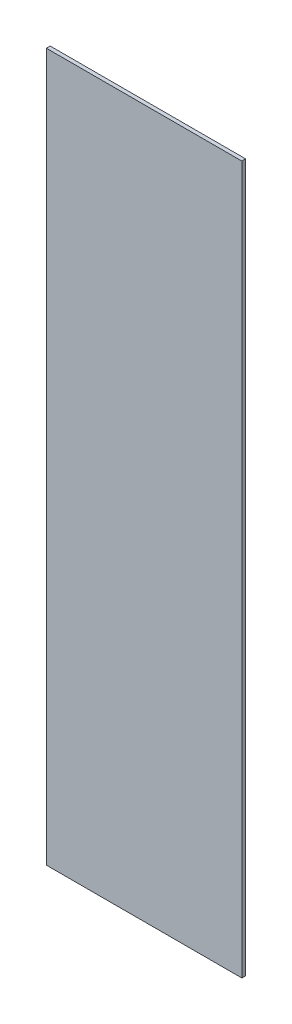
SolidWorks part; units mm, degrees
ref_plane "Front Plane" through (0, 0, 0) normal (0, 0, 1) x (1, 0, 0)
ref_plane "Top Plane" through (0, 0, 0) normal (0, 1, 0) x (1, 0, 0)
ref_plane "Right Plane" through (0, 0, 0) normal (1, 0, 0) x (0, 0, -1)
sketch "Sketch1" plane through (0, 0, 0) normal (0, 0, 1) x (1, 0, 0)
  line L1 (0, 0) -> (81.4, 0)
  line L2 (0, 0) -> (0, 294.64)
  line L4 (81.4, 0) -> (81.4, 294.64)
  line L7 (0, 294.64) -> (81.4, 294.64) construction
  line L9 (0, 294.64) -> (81.4, 294.64)
  dimension "D1" = 81.4
  dimension "D2" = 294.64
extrude "Boss-Extrude1" add sketch "Sketch1" along normal blind 1.5875
sketch "Sketch2" plane through (0, 0, 1.5875) normal (0, 0, 1) x (1, 0, 0)
  line L0 (0, 294.64) -> (0, 0) construction
  line L7 (81.4, 294.64) -> (0, 294.64)
  line L8 (81.4, 294.64) -> (81.4, 307.34)
  line L9 (43.875, 320.04) -> (37.525, 320.04)
  line L10 (0, 294.64) -> (0, 307.34)
  line L11 (43.875, 320.04) -> (56.575, 307.34)
  line L12 (56.575, 307.34) -> (81.4, 307.34)
  line L13 (40.7, 320.04) -> (40.7, 294.64) construction
  line L16 (0, 307.34) -> (24.825, 307.34)
  line L17 (37.525, 320.04) -> (24.825, 307.34)
  dimension "D2" = 12.7
  dimension "D3" = 12.7
  dimension "D1" = 25.4
  dimension "D4" = 6.35
  dimension "D5" = 135
  dimension "D6" = 135
extrude "Boss-Extrude2" [suppressed] add sketch "Sketch2" against normal up to surface (1.5875 mm away)
sketch "Sketch3" [suppressed] plane through (0, 0, 0) normal (0, 0, -1) x (-1, 0, 0)
  line L0 (-40.7, 320.04) -> (-40.7, 0) construction
  line L1 (-43.875, 320.04) -> (-37.525, 320.04) construction
  line L2 (0, 0) -> (-81.4, 0) construction
fillet "Fillet3" [suppressed] radius 6.35
